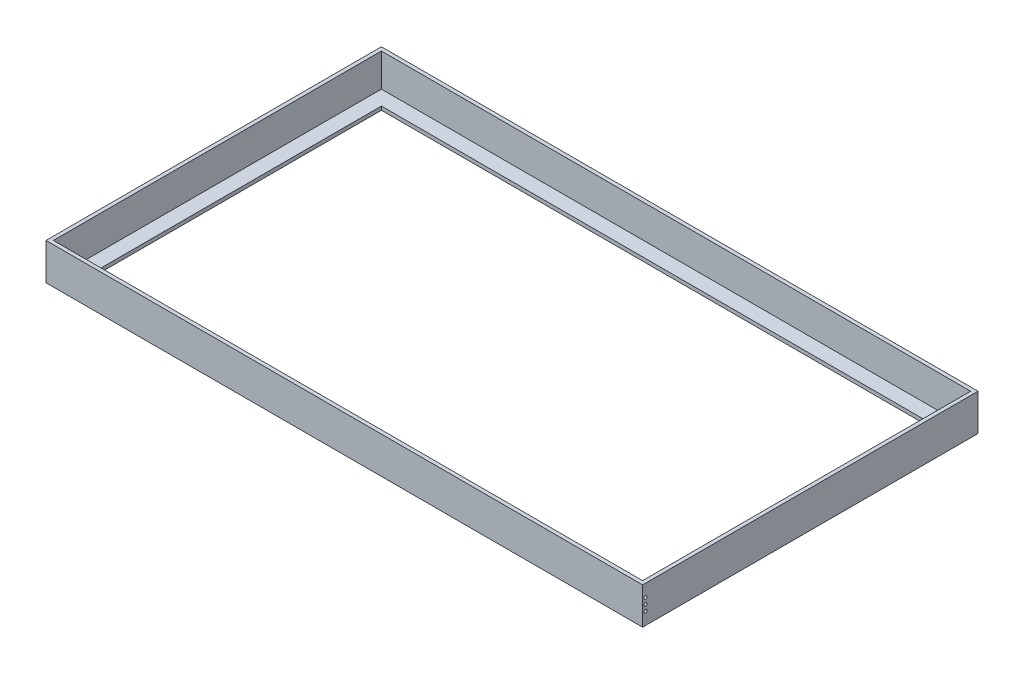
SolidWorks part; units mm, degrees
ref_plane "Front Plane" through (0, 0, 0) normal (0, 0, 1) x (1, 0, 0)
ref_plane "Top Plane" through (0, 0, 0) normal (0, 1, 0) x (1, 0, 0)
ref_plane "Right Plane" through (0, 0, 0) normal (1, 0, 0) x (0, 0, -1)
sketch "Sketch2" plane through (0, 0, 0) normal (0, 1, 0) x (1, 0, 0)
  line L1 (0, 0) -> (1626.4, 0)
  line L2 (0, 0) -> (0, 914.4)
  line L3 (0, 914.4) -> (1626.4, 914.4)
  line L4 (1626.4, 0) -> (1626.4, 914.4)
  dimension "D1" = 1626.4
  dimension "D2" = 914.4
extrude "Boss-Extrude1" add sketch "Sketch2" along normal blind 100
shell "Shell1" thickness 10
sketch "Sketch3" plane through (0, 10, 0) normal (0, 1, 0) x (1, 0, 0)
  line L0 (10, 904.4) -> (10, 10) construction
  line L1 (50, 864.4) -> (1576.4, 864.4)
  line L2 (50, 864.4) -> (50, 50)
  line L3 (50, 50) -> (1576.4, 50)
  line L4 (1576.4, 864.4) -> (1576.4, 50)
  line L5 (1616.4, 904.4) -> (10, 904.4) construction
  line L6 (1616.4, 10) -> (1616.4, 904.4) construction
  line L7 (10, 10) -> (1616.4, 10) construction
  dimension "D1" = 40
  dimension "D2" = 40
  dimension "D3" = 40
  dimension "D4" = 40
extrude "Cut-Extrude1" cut sketch "Sketch3" against normal through all
sketch "Sketch5" plane through (1626.4, 0, 0) normal (1, 0, 0) x (0, 0, -1)
  line L0 (0, 100) -> (0, 0) construction
  circle A0 centre (7.85, 50) radius 4
  dimension "D1" = 8
  dimension "D2" = 7.85
extrude "Cut-Extrude2" cut sketch "Sketch5" against normal through all
sketch "Sketch6" plane through (1626.4, 0, 0) normal (1, 0, 0) x (0, 0, -1)
  line L0 (0, 100) -> (0, 0) construction
  circle A0 centre (7.85, 66.28) radius 4
  circle A1 centre (7.85, 50) radius 4 construction
  dimension "D1" = 7.85
  dimension "D2" = 16.28
  dimension "D3" = 8
extrude "Cut-Extrude3" cut sketch "Sketch6" against normal through all
sketch "Sketch7" plane through (1626.4, 0, 0) normal (1, 0, 0) x (0, 0, -1)
  line L0 (0, 100) -> (0, 0) construction
  circle A0 centre (7.85, 33.72) radius 4
  circle A2 centre (7.85, 50) radius 4 construction
  dimension "D1" = 7.85
  dimension "D2" = 8
  dimension "D3" = 16.28
extrude "Cut-Extrude4" cut sketch "Sketch7" against normal through all
